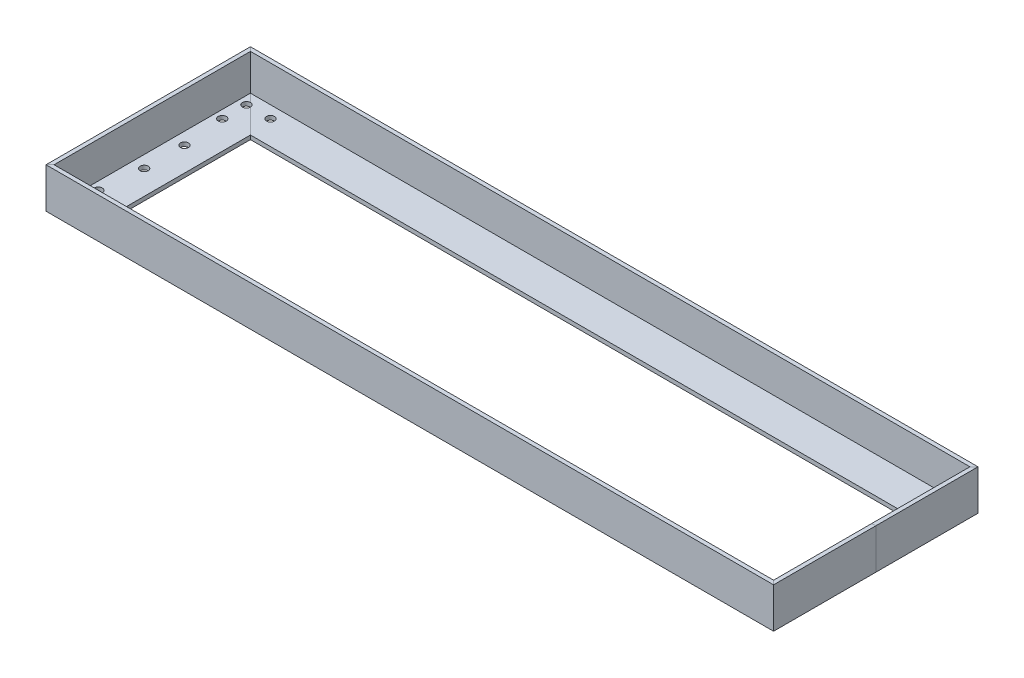
SolidWorks part; units mm, degrees
material "AISI Type A2 Tool Steel"
other "Profile Properties"
ref_plane "Front Plane" through (0, 0, 0) normal (0, 0, 1) x (1, 0, 0)
ref_plane "Top Plane" through (0, 0, 0) normal (0, 1, 0) x (1, 0, 0)
ref_plane "Right Plane" through (0, 0, 0) normal (1, 0, 0) x (0, 0, -1)
sketch "Sketch1" plane through (0, 0, 0) normal (0, 1, 0) x (1, 0, 0)
  line L1 (-450, -125) -> (450, -125)
  line L2 (-450, -125) -> (-450, 125)
  line L3 (-450, 125) -> (450, 125)
  line L4 (450, -125) -> (450, 125)
  line L5 (-450, -125) -> (450, 125) construction
  line L6 (-450, 125) -> (450, -125) construction
  point P0 (0, 0)
  dimension "D1" = 250
  dimension "D2" = 900
sketch "Sketch2" plane through (0, 0, 0) normal (0, 0, 1) x (1, 0, 0)
  line L0 (402, -2.5) -> (452, -2.5)
  line L3 (452, -2.5) -> (452, 47.5)
  line L4 (452, 47.5) -> (447, 47.5)
  line L5 (447, 47.5) -> (447, 2.5)
  line L6 (447, 2.5) -> (402, 2.5)
  line L7 (402, 2.5) -> (402, -2.5)
  line L8 (-450, 0) -> (450, 0) construction
  dimension "D1" = 50
  dimension "D2" = 50
  dimension "D3" = 5
  dimension "D4" = 5
  dimension "D5" = 452
  dimension "D6" = 2.5
sweep "Sweep3" add profiles "Sketch2" path "Sketch1"
sketch "Sketch5" plane through (0, 0, 0) normal (0, 1, 0) x (1, 0, 0)
  line L0 (-402, 77) -> (402, 77) construction
  line L1 (-402, -77) -> (-402, 77) construction
  line L8 (-447, -122) -> (-447, 122) construction
  line L9 (-27.5, 0) -> (27.5, 0) construction
  line L10 (0, -27.5) -> (0, 27.5) construction
  circle A0 centre (-437, 107) radius 5
  circle A1 centre (-407, 107) radius 5
  circle A2 centre (-432, 25) radius 5
  circle A3 centre (-437, 77) radius 5
  circle A4 centre (-407, -107) radius 5
  circle A5 centre (-437, -107) radius 5
  circle A6 centre (-437, -77) radius 5
  circle A7 centre (-432, -25) radius 5
  circle A8 centre (432, -25) radius 5
  circle A9 centre (437, -77) radius 5
  circle A10 centre (437, -107) radius 5
  circle A11 centre (407, -107) radius 5
  circle A12 centre (437, 77) radius 5
  circle A13 centre (432, 25) radius 5
  circle A14 centre (407, 107) radius 5
  circle A15 centre (437, 107) radius 5
  dimension "D1" = 10
  dimension "D2" = 30
  dimension "D3" = 10
  dimension "D4" = 30
  dimension "D5" = 10
  dimension "D6" = 30
  dimension "D7" = 30
  dimension "D8" = 25
extrude "Cut-Extrude1" cut sketch "Sketch5" against normal through all both and the other way through all
